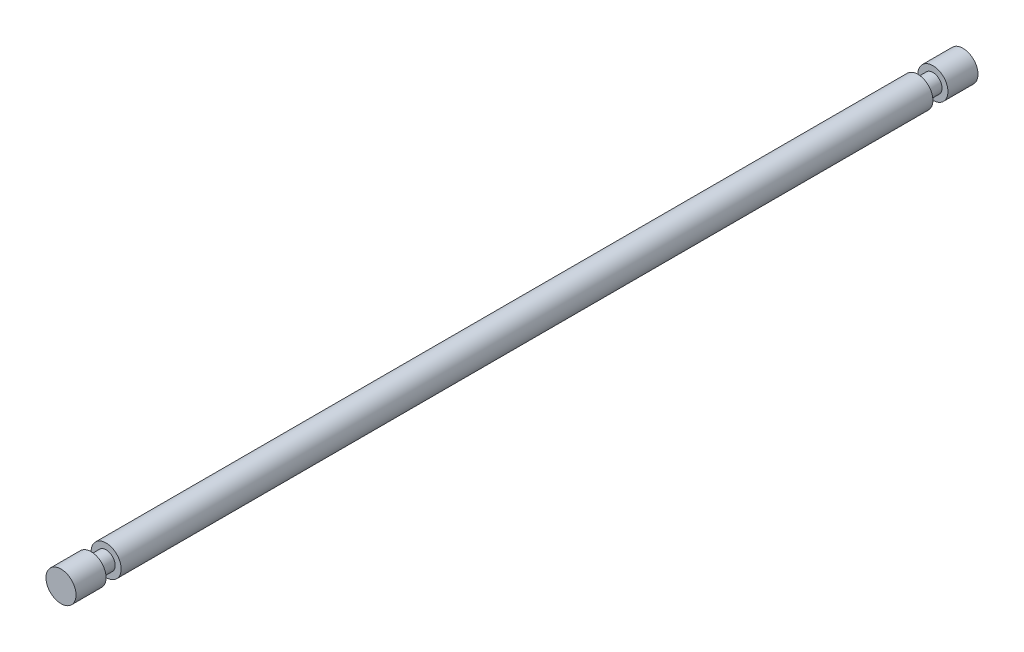
SolidWorks part; units mm, degrees
ref_plane "Front Plane" through (0, 0, 0) normal (0, 0, 1) x (1, 0, 0)
ref_plane "Top Plane" through (0, 0, 0) normal (0, 1, 0) x (1, 0, 0)
ref_plane "Right Plane" through (0, 0, 0) normal (1, 0, 0) x (0, 0, -1)
sketch "Sketch2" plane through (0, 0, 0) normal (0, 1, 0) x (1, 0, 0)
  line L1 (0, 0) -> (1.27, 0)
  line L2 (0, 0) -> (0, 76.2)
  line L3 (0, 76.2) -> (1.27, 76.2)
  line L4 (1.27, 0) -> (1.27, 76.2)
  dimension "D1" = 1.27
  dimension "D2" = 76.2
revolve "Revolve1" add sketch "Sketch2" angle 360 about L2
sketch "Sketch3" plane through (0, 0, 0) normal (0, 1, 0) x (1, 0, 0)
  line L0 (1.27, 2.54) -> (0.7706, 2.54)
  line L1 (1.27, 0) -> (1.27, 76.2) construction
  line L2 (0.7706, 2.54) -> (0.7706, 3.81)
  line L3 (0.7706, 3.81) -> (1.27, 3.81)
  line L4 (1.27, 3.81) -> (1.27, 2.54)
  line L5 (-1.27, 0) -> (1.27, 0) construction
  line L6 (0, 0) -> (0, 4.6043) construction
  dimension "D1" = 0.4994
  dimension "D2" = 2.54
  dimension "D3" = 1.27
revolve "Cut-Revolve1" cut sketch "Sketch3" angle 360 about L6
ref_plane "Mirror Point" through (0, 0, -38.1) normal (0, 0, 1) x (1, 0, 0)
mirror "Mirror1" about plane through (0, 0, -38.1) normal (0, 0, 1) of "Cut-Revolve1"
